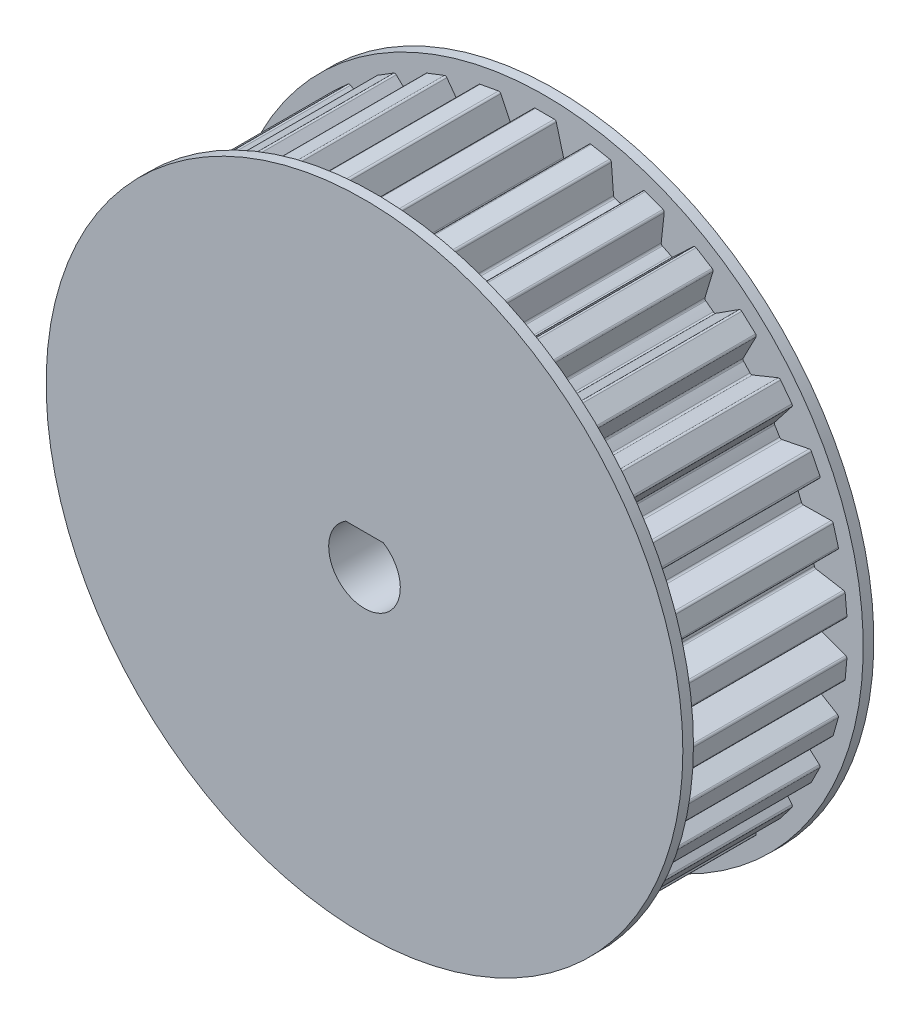
SolidWorks part; units mm, degrees
ref_plane "Plan de face" through (0, 0, 0) normal (0, 0, 1) x (1, 0, 0)
ref_plane "Plan de dessus" through (0, 0, 0) normal (0, 1, 0) x (1, 0, 0)
ref_plane "Plan de droite" through (0, 0, 0) normal (1, 0, 0) x (0, 0, -1)
sketch "Esquisse1" plane through (0, 0, 0) normal (0, 0, 1) x (1, 0, 0)
  line L0 (0, 21.7728) -> (0, 34.0588) construction
  line L1 (-1.0353, 28.5) -> (1.0353, 28.5)
  line L2 (1.0353, 28.5) -> (1.7888, 25.6878)
  line L3 (-25.75, 0) -> (30.4929, 0) construction
  line L4 (0, -28.5) -> (1.0353, -28.5)
  line L5 (0, 28.5) -> (1.7626, 21.9219) construction
  line L6 (-1.0353, 28.5) -> (-1.7888, 25.6878)
  line L7 (4.2192, 28.205) -> (2.9618, 25.5791)
  line L8 (4.2192, 28.205) -> (6.2545, 27.8245)
  line L9 (6.2545, 27.8245) -> (6.4785, 24.9217)
  line L10 (9.33, 26.9494) -> (7.6115, 24.5993)
  line L11 (9.33, 26.9494) -> (11.2608, 26.2015)
  line L12 (11.2608, 26.2015) -> (10.9475, 23.307)
  line L13 (14.1231, 24.7762) -> (12.002, 22.7819)
  line L14 (14.1231, 24.7762) -> (15.8835, 23.6862)
  line L15 (15.8835, 23.6862) -> (15.0438, 20.8985)
  line L16 (18.4352, 21.7592) -> (15.9838, 20.1886)
  line L17 (18.4352, 21.7592) -> (19.9654, 20.3643)
  line L18 (19.9654, 20.3643) -> (18.6277, 17.7784)
  line L19 (22.1196, 18.0013) -> (19.4213, 16.9079)
  line L20 (22.1196, 18.0013) -> (23.3674, 16.3489)
  line L21 (23.3674, 16.3489) -> (21.5773, 14.0529)
  line L22 (25.0507, 13.6303) -> (22.1974, 13.0513)
  line L23 (25.0507, 13.6303) -> (25.9736, 11.7768)
  line L24 (25.9736, 11.7768) -> (23.7921, 9.8488)
  line L25 (27.1287, 8.7952) -> (24.2176, 8.7503)
  line L26 (27.1287, 8.7952) -> (27.6953, 6.8036)
  line L27 (27.6953, 6.8036) -> (25.1967, 5.3093)
  line L28 (28.2829, 3.6605) -> (25.4132, 4.1513)
  line L29 (28.2829, 3.6605) -> (28.4739, 1.5988)
  line L30 (28.4739, 1.5988) -> (25.7433, 0.589)
  line L31 (28.4739, -1.5988) -> (25.7433, -0.589)
  line L32 (28.4739, -1.5988) -> (28.2829, -3.6605)
  line L33 (28.2829, -3.6605) -> (25.4132, -4.1513)
  line L34 (27.6953, -6.8036) -> (25.1967, -5.3093)
  line L35 (27.6953, -6.8036) -> (27.1287, -8.7952)
  line L36 (27.1287, -8.7952) -> (24.2176, -8.7503)
  line L37 (25.9736, -11.7768) -> (23.7921, -9.8488)
  line L38 (25.9736, -11.7768) -> (25.0507, -13.6303)
  line L39 (25.0507, -13.6303) -> (22.1974, -13.0513)
  line L40 (23.3674, -16.3489) -> (21.5773, -14.0529)
  line L41 (23.3674, -16.3489) -> (22.1196, -18.0013)
  line L42 (22.1196, -18.0013) -> (19.4213, -16.9079)
  line L43 (19.9654, -20.3643) -> (18.6277, -17.7784)
  line L44 (19.9654, -20.3643) -> (18.4352, -21.7592)
  line L45 (18.4352, -21.7592) -> (15.9838, -20.1886)
  line L46 (15.8835, -23.6862) -> (15.0438, -20.8985)
  line L47 (15.8835, -23.6862) -> (14.1231, -24.7762)
  line L48 (14.1231, -24.7762) -> (12.002, -22.7819)
  line L49 (11.2608, -26.2015) -> (10.9475, -23.307)
  line L50 (11.2608, -26.2015) -> (9.33, -26.9494)
  line L51 (9.33, -26.9494) -> (7.6115, -24.5993)
  line L52 (6.2545, -27.8245) -> (6.4785, -24.9217)
  line L53 (6.2545, -27.8245) -> (4.2192, -28.205)
  line L54 (4.2192, -28.205) -> (2.9618, -25.5791)
  line L55 (1.0353, -28.5) -> (1.7888, -25.6878)
  line L56 (1.0353, -28.5) -> (-1.0353, -28.5)
  line L57 (-1.0353, -28.5) -> (-1.7888, -25.6878)
  line L58 (-4.2192, -28.205) -> (-2.9618, -25.5791)
  line L59 (-4.2192, -28.205) -> (-6.2545, -27.8245)
  line L60 (-6.2545, -27.8245) -> (-6.4785, -24.9217)
  line L61 (-9.33, -26.9494) -> (-7.6115, -24.5993)
  line L62 (-9.33, -26.9494) -> (-11.2608, -26.2015)
  line L63 (-11.2608, -26.2015) -> (-10.9475, -23.307)
  line L64 (-14.1231, -24.7762) -> (-12.002, -22.7819)
  line L65 (-14.1231, -24.7762) -> (-15.8835, -23.6862)
  line L66 (-15.8835, -23.6862) -> (-15.0438, -20.8985)
  line L67 (-18.4352, -21.7592) -> (-15.9838, -20.1886)
  line L68 (-18.4352, -21.7592) -> (-19.9654, -20.3643)
  line L69 (-19.9654, -20.3643) -> (-18.6277, -17.7784)
  line L70 (-22.1196, -18.0013) -> (-19.4213, -16.9079)
  line L71 (-22.1196, -18.0013) -> (-23.3674, -16.3489)
  line L72 (-23.3674, -16.3489) -> (-21.5773, -14.0529)
  line L73 (-25.0507, -13.6303) -> (-22.1974, -13.0513)
  line L74 (-25.0507, -13.6303) -> (-25.9736, -11.7768)
  line L75 (-25.9736, -11.7768) -> (-23.7921, -9.8488)
  line L76 (-27.1287, -8.7952) -> (-24.2176, -8.7503)
  line L77 (-27.1287, -8.7952) -> (-27.6953, -6.8036)
  line L78 (-27.6953, -6.8036) -> (-25.1967, -5.3093)
  line L79 (-28.2829, -3.6605) -> (-25.4132, -4.1513)
  line L80 (-28.2829, -3.6605) -> (-28.4739, -1.5988)
  line L81 (-28.4739, -1.5988) -> (-25.7433, -0.589)
  line L82 (-28.4739, 1.5988) -> (-25.7433, 0.589)
  line L83 (-28.4739, 1.5988) -> (-28.2829, 3.6605)
  line L84 (-28.2829, 3.6605) -> (-25.4132, 4.1513)
  line L85 (-27.6953, 6.8036) -> (-25.1967, 5.3093)
  line L86 (-27.6953, 6.8036) -> (-27.1287, 8.7952)
  line L87 (-27.1287, 8.7952) -> (-24.2176, 8.7503)
  line L88 (-25.9736, 11.7768) -> (-23.7921, 9.8488)
  line L89 (-25.9736, 11.7768) -> (-25.0507, 13.6303)
  line L90 (-25.0507, 13.6303) -> (-22.1974, 13.0513)
  line L91 (-23.3674, 16.3489) -> (-21.5773, 14.0529)
  line L92 (-23.3674, 16.3489) -> (-22.1196, 18.0013)
  line L93 (-22.1196, 18.0013) -> (-19.4213, 16.9079)
  line L94 (-19.9654, 20.3643) -> (-18.6277, 17.7784)
  line L95 (-19.9654, 20.3643) -> (-18.4352, 21.7592)
  line L96 (-18.4352, 21.7592) -> (-15.9838, 20.1886)
  line L97 (-15.8835, 23.6862) -> (-15.0438, 20.8985)
  line L98 (-15.8835, 23.6862) -> (-14.1231, 24.7762)
  line L99 (-14.1231, 24.7762) -> (-12.002, 22.7819)
  line L100 (-11.2608, 26.2015) -> (-10.9475, 23.307)
  line L101 (-11.2608, 26.2015) -> (-9.33, 26.9494)
  line L102 (-9.33, 26.9494) -> (-7.6115, 24.5993)
  line L103 (-6.2545, 27.8245) -> (-6.4785, 24.9217)
  line L104 (-6.2545, 27.8245) -> (-4.2192, 28.205)
  line L105 (-4.2192, 28.205) -> (-2.9618, 25.5791)
  arc A1 (-1.7888, 25.6878) -> (-2.9618, 25.5791) centre (0, 0) ccw
  arc A2 (-6.4785, 24.9217) -> (-7.6115, 24.5993) centre (0, 0) ccw
  arc A3 (-10.9475, 23.307) -> (-12.002, 22.7819) centre (0, 0) ccw
  arc A4 (-15.0438, 20.8985) -> (-15.9838, 20.1886) centre (0, 0) ccw
  arc A5 (-18.6277, 17.7784) -> (-19.4213, 16.9079) centre (0, 0) ccw
  arc A6 (-21.5773, 14.0529) -> (-22.1974, 13.0513) centre (0, 0) ccw
  arc A7 (-23.7921, 9.8488) -> (-24.2176, 8.7503) centre (0, 0) ccw
  arc A8 (-25.1967, 5.3093) -> (-25.4132, 4.1513) centre (0, 0) ccw
  arc A9 (-25.7433, 0.589) -> (-25.7433, -0.589) centre (0, 0) ccw
  arc A10 (-25.4132, -4.1513) -> (-25.1967, -5.3093) centre (0, 0) ccw
  arc A11 (-24.2176, -8.7503) -> (-23.7921, -9.8488) centre (0, 0) ccw
  arc A12 (-22.1974, -13.0513) -> (-21.5773, -14.0529) centre (0, 0) ccw
  arc A13 (-19.4213, -16.9079) -> (-18.6277, -17.7784) centre (0, 0) ccw
  arc A14 (-15.9838, -20.1886) -> (-15.0438, -20.8985) centre (0, 0) ccw
  arc A15 (-12.002, -22.7819) -> (-10.9475, -23.307) centre (0, 0) ccw
  arc A16 (-7.6115, -24.5993) -> (-6.4785, -24.9217) centre (0, 0) ccw
  arc A17 (-2.9618, -25.5791) -> (-1.7888, -25.6878) centre (0, 0) ccw
  arc A18 (1.7888, -25.6878) -> (2.9618, -25.5791) centre (0, 0) ccw
  arc A19 (6.4785, -24.9217) -> (7.6115, -24.5993) centre (0, 0) ccw
  arc A20 (10.9475, -23.307) -> (12.002, -22.7819) centre (0, 0) ccw
  arc A21 (15.0438, -20.8985) -> (15.9838, -20.1886) centre (0, 0) ccw
  arc A22 (18.6277, -17.7784) -> (19.4213, -16.9079) centre (0, 0) ccw
  arc A23 (21.5773, -14.0529) -> (22.1974, -13.0513) centre (0, 0) ccw
  arc A24 (23.7921, -9.8488) -> (24.2176, -8.7503) centre (0, 0) ccw
  arc A25 (25.1967, -5.3093) -> (25.4132, -4.1513) centre (0, 0) ccw
  arc A26 (25.7433, -0.589) -> (25.7433, 0.589) centre (0, 0) ccw
  arc A27 (25.4132, 4.1513) -> (25.1967, 5.3093) centre (0, 0) ccw
  arc A28 (24.2176, 8.7503) -> (23.7921, 9.8488) centre (0, 0) ccw
  arc A29 (22.1974, 13.0513) -> (21.5773, 14.0529) centre (0, 0) ccw
  arc A30 (19.4213, 16.9079) -> (18.6277, 17.7784) centre (0, 0) ccw
  arc A31 (15.9838, 20.1886) -> (15.0438, 20.8985) centre (0, 0) ccw
  arc A32 (12.002, 22.7819) -> (10.9475, 23.307) centre (0, 0) ccw
  arc A33 (7.6115, 24.5993) -> (6.4785, 24.9217) centre (0, 0) ccw
  arc A34 (2.9618, 25.5791) -> (1.7888, 25.6878) centre (0, 0) ccw
  point P150 (0, 0)
  dimension "D2" = 51.5
  dimension "D3" = 15
  dimension "D4" = 57
  dimension "D5" = 1
  dimension "D6" = 34
extrude "Boss.-Extru.1" add sketch "Esquisse1" along normal blind 16
sketch "Esquisse2" [suppressed] plane through (0, 0, 19) normal (0, 0, 1) x (1, 0, 0)
  circle A0 centre (0, 0) radius 30
  dimension "D1" = 60
extrude "Boss.-Extru.2" [suppressed] add sketch "Esquisse2" along normal blind 2
sketch "Esquisse3" plane through (0, 0, 16) normal (0, 0, 1) x (1, 0, 0)
  circle A0 centre (0, 0) radius 30
  dimension "D1" = 60
extrude "Boss.-Extru.3" add sketch "Esquisse3" along normal blind 1
sketch "Esquisse5" plane through (0, 0, 0) normal (0, 0, -1) x (-1, 0, 0)
  circle A0 centre (0, 0) radius 30
extrude "Boss.-Extru.4" add sketch "Esquisse5" along normal blind 1
fillet "Congé1" radius 0.2 130 edges at (-2.9618, 25.5791, 8) (-1.7888, 25.6878, 8) (1.0353, 28.5, 8) (-4.2192, 28.205, 8) (-7.6115, 24.5993, 8) (-6.2545, 27.8245, 8) (-6.4785, 24.9217, 8) (-9.33, 26.9494, 8) (-11.2608, 26.2015, 8) (-12.002, 22.7819, 8) (-10.9475, 23.307, 8) (-14.1231, 24.7762, 8) (-15.8835, 23.6862, 8) (-15.9838, 20.1886, 8) (-15.0438, 20.8985, 8) (-18.4352, 21.7592, 8) (-19.9654, 20.3643, 8) (-18.6277, 17.7784, 8) (-19.4213, 16.9079, 8) (-22.1196, 18.0013, 8) (-21.5773, 14.0529, 8) (-22.1974, 13.0513, 8) (-25.9736, 11.7768, 8) (-23.7921, 9.8488, 8) (-27.1287, 8.7952, 8) (-27.6953, 6.8036, 8) (-25.1967, 5.3093, 8) (-25.4132, 4.1513, 8) (-28.2829, 3.6605, 8) (-28.4739, 1.5988, 8) (-25.7433, 0.589, 8) (-25.7433, -0.589, 8) (-28.4739, -1.5988, 8) (-28.2829, -3.6605, 8) (-25.4132, -4.1513, 8) (-25.1967, -5.3093, 8) (-27.6953, -6.8036, 8) (-27.1287, -8.7952, 8) (-24.2176, -8.7503, 8) (-23.7921, -9.8488, 8) (-25.9736, -11.7768, 8) (-25.0507, -13.6303, 8) (-22.1974, -13.0513, 8) (-21.5773, -14.0529, 8) (-23.3674, -16.3489, 8) (-22.1196, -18.0013, 8) (-19.4213, -16.9079, 8) (-18.6277, -17.7784, 8) (-19.9654, -20.3643, 8) (-18.4352, -21.7592, 8) (-15.9838, -20.1886, 8) (-15.0438, -20.8985, 8) (-15.8835, -23.6862, 8) (-14.1231, -24.7762, 8) (-12.002, -22.7819, 8) (-10.9475, -23.307, 8) (-11.2608, -26.2015, 8) (-9.33, -26.9494, 8) (-7.6115, -24.5993, 8) (-6.4785, -24.9217, 8) (-6.2545, -27.8245, 8) (-2.9618, -25.5791, 8) (-1.7888, -25.6878, 8) (-1.0353, -28.5, 8) (2.9618, -25.5791, 8) (1.0353, -28.5, 8) (1.7888, -25.6878, 8) (4.2192, -28.205, 8) (6.2545, -27.8245, 8) (6.4785, -24.9217, 8) (9.33, -26.9494, 8) (11.2608, -26.2015, 8) (10.9475, -23.307, 8) (12.002, -22.7819, 8) (14.1231, -24.7762, 8) (15.8835, -23.6862, 8) (15.0438, -20.8985, 8) (15.9838, -20.1886, 8) (18.4352, -21.7592, 8) (19.9654, -20.3643, 8) (19.4213, -16.9079, 8) (18.6277, -17.7784, 8) (22.1196, -18.0013, 8) (23.3674, -16.3489, 8) (21.5773, -14.0529, 8) (22.1974, -13.0513, 8) (25.0507, -13.6303, 8) (25.9736, -11.7768, 8) (23.7921, -9.8488, 8) (24.2176, -8.7503, 8) (27.1287, -8.7952, 8) (27.6953, -6.8036, 8) (25.1967, -5.3093, 8) (25.4132, -4.1513, 8) (28.2829, -3.6605, 8) (28.4739, -1.5988, 8) (25.7433, -0.589, 8) (25.7433, 0.589, 8) (28.4739, 1.5988, 8) (28.2829, 3.6605, 8) (25.4132, 4.1513, 8) (25.1967, 5.3093, 8) (27.6953, 6.8036, 8) (27.1287, 8.7952, 8) (24.2176, 8.7503, 8) (23.7921, 9.8488, 8) (25.9736, 11.7768, 8) (25.0507, 13.6303, 8) (22.1974, 13.0513, 8) (21.5773, 14.0529, 8) (23.3674, 16.3489, 8) (22.1196, 18.0013, 8) (19.9654, 20.3643, 8) (19.4213, 16.9079, 8) (18.6277, 17.7784, 8) (15.0438, 20.8985, 8) (15.9838, 20.1886, 8) (10.9475, 23.307, 8) (7.6115, 24.5993, 8) (6.4785, 24.9217, 8) (18.4352, 21.7592, 8) (15.8835, 23.6862, 8) (14.1231, 24.7762, 8) (12.002, 22.7819, 8) (11.2608, 26.2015, 8) (9.33, 26.9494, 8) (6.2545, 27.8245, 8) (4.2192, 28.205, 8) (2.9618, 25.5791, 8) (1.7888, 25.6878, 8)
sketch "Esquisse6" plane through (0, 0, 17) normal (0, 0, 1) x (1, 0, 0)
  line L0 (0, 3.175) -> (0, -4.6284) construction
  line L5 (-6.4633, 0) -> (5.3753, 0) construction
  line L7 (-1.7678, 2.875) -> (1.7678, 2.875)
  arc A2 (-1.7678, 2.875) -> (1.7678, 2.875) centre (0, 0) ccw
  point P0 (0, 0)
  point P1 (1.7103, 2.675)
  point P12 (0, 2.675)
  point P13 (-1.7103, 2.675)
extrude "Enlèv. mat.-Extru.1" cut sketch "Esquisse6" against normal through all
